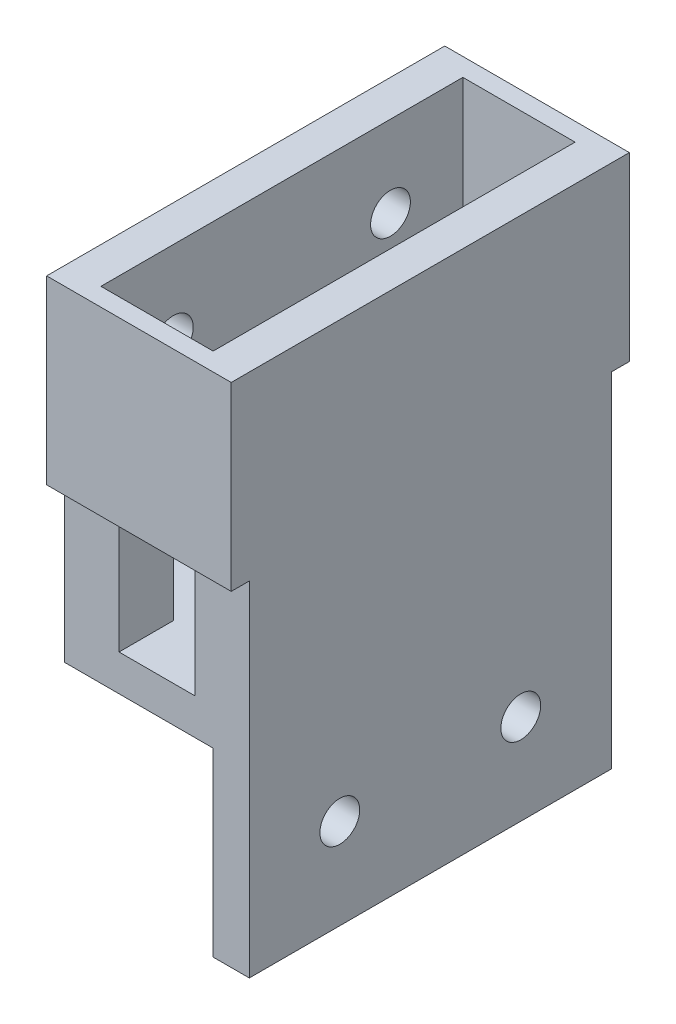
SolidWorks part; units mm, degrees
material "ABS"
ref_plane "Front Plane" through (0, 0, 0) normal (0, 0, 1) x (1, 0, 0)
ref_plane "Top Plane" through (0, 0, 0) normal (0, 1, 0) x (1, 0, 0)
ref_plane "Right Plane" through (0, 0, 0) normal (1, 0, 0) x (0, 0, -1)
sketch "Sketch1" plane through (0, 0, 0) normal (0, 0, 1) x (1, 0, 0)
  line L0 (0, 11) -> (0, -8)
  line L1 (0, 11) -> (2, 11)
  line L2 (2, 11) -> (2, 2)
  line L3 (2, 2) -> (3, 2)
  line L4 (8.2, 2) -> (8.2, 11)
  line L5 (8.2, 11) -> (10.2, 11)
  line L6 (10.2, 11) -> (10.2, -6)
  line L7 (10.2, -6) -> (10.2, -18)
  line L8 (3, 2) -> (3, -6)
  line L9 (3, -6) -> (7.2, -6)
  line L10 (7.2, -6) -> (7.2, 2)
  line L11 (7.2, 2) -> (8.2, 2)
  line L12 (10.2, -18) -> (8.2, -18)
  line L14 (8.2, -18) -> (8.2, -8)
  line L16 (0, -8) -> (8.2, -8)
  dimension "D1" = 2
  dimension "D2" = 9
  dimension "D3" = 8
  dimension "D4" = 2
  dimension "D5" = 2
  dimension "D6" = 10
  dimension "D7" = 6.2
extrude "Boss-Extrude1" add sketch "Sketch1" along normal blind 20
sketch "Sketch2" plane through (0, 0, 0) normal (-1, 0, 0) x (0, 0, 1)
  line L0 (20, -8) -> (0, -8) construction
  line L1 (3, -6) -> (17, -6)
  line L2 (3, -6) -> (3, -2)
  line L3 (3, -2) -> (17, -2)
  line L4 (17, -6) -> (17, -2)
  line L5 (0, 11) -> (0, -8) construction
  line L6 (20, 11) -> (20, -8) construction
  dimension "D1" = 2
  dimension "D2" = 3
  dimension "D3" = 3
  dimension "D4" = 4
extrude "Cut-Extrude1" cut sketch "Sketch2" against normal up to surface (3 mm away) up to face at (3, -2, 10)
sketch "Sketch9" plane through (0, 11, 0) normal (0, 1, 0) x (1, 0, 0)
  line L0 (0, 0) -> (10.2, 0)
  line L1 (10.2, 0) -> (10.2, 1)
  line L2 (10.2, 1) -> (0, 1)
  line L3 (0, 1) -> (0, 0)
  line L4 (10.2, -20) -> (0, -20)
  line L5 (0, -20) -> (0, -21)
  line L6 (0, -21) -> (10.2, -21)
  line L7 (10.2, -21) -> (10.2, -20)
  dimension "D1" = 1
  dimension "D2" = 1
extrude "Boss-Extrude11" add sketch "Sketch9" against normal blind 10
sketch "Sketch10" plane through (0, 0, 0) normal (-1, 0, 0) x (0, 0, 1)
  line L0 (-4.7151, 6.5) -> (28.8565, 6.5) construction
  line L1 (21, 11) -> (-1, 11) construction
  line L2 (-1, 1) -> (-1, 11) construction
  line L4 (21, 1) -> (21, 11) construction
  circle A0 centre (4, 6.5) radius 1.1
  circle A1 centre (16, 6.5) radius 1.1
  dimension "D4" = 2.2
  dimension "D5" = 2.2
  dimension "D1" = 4.5
  dimension "D2" = 5
  dimension "D3" = 5
extrude "Cut-Extrude2" cut sketch "Sketch10" against normal blind 5
sketch "Sketch11" plane through (8.2, 0, 0) normal (-1, 0, 0) x (0, 0, 1)
  line L0 (-2.6053, -13) -> (32.6053, -13) construction
  line L1 (20, -18) -> (0, -18) construction
  line L2 (0, -8) -> (0, -18) construction
  line L3 (20, -8) -> (20, -18) construction
  circle A0 centre (5, -13) radius 1.1
  circle A1 centre (15, -13) radius 1.1
  point P4 (10, -18)
  dimension "D4" = 2.2
  dimension "D5" = 2.2
  dimension "D1" = 5
  dimension "D2" = 5
  dimension "D3" = 5
extrude "Cut-Extrude3" cut sketch "Sketch11" against normal blind 5
